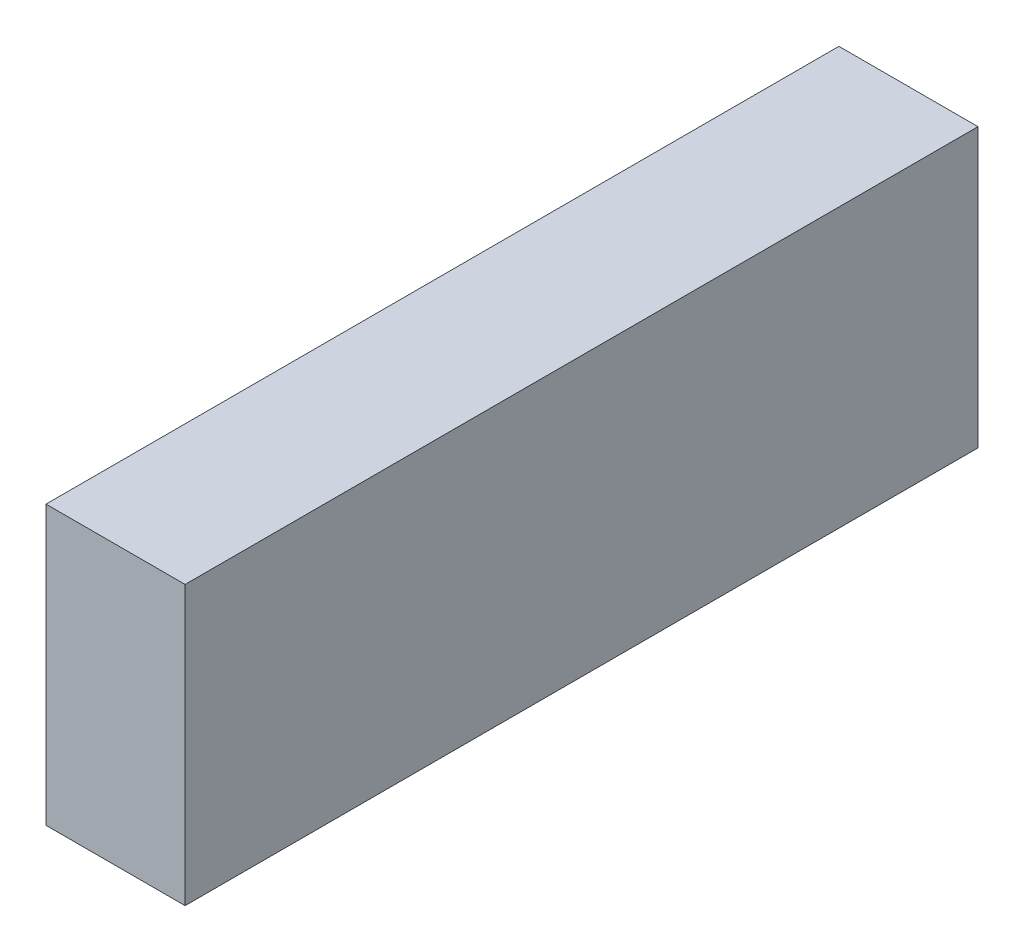
SolidWorks part; units mm, degrees
ref_plane "Front Plane" through (0, 0, 0) normal (0, 0, 1) x (1, 0, 0)
ref_plane "Top Plane" through (0, 0, 0) normal (0, 1, 0) x (1, 0, 0)
ref_plane "Right Plane" through (0, 0, 0) normal (1, 0, 0) x (0, 0, -1)
sketch "Sketch1" plane through (0, 0, 0) normal (1, 0, 0) x (0, 0, -1)
  line L1 (0, 0) -> (57, 0)
  line L2 (0, 0) -> (0, 20)
  line L3 (0, 20) -> (57, 20)
  line L4 (57, 0) -> (57, 20)
extrude "Boss-Extrude1" add sketch "Sketch1" along normal blind 10
